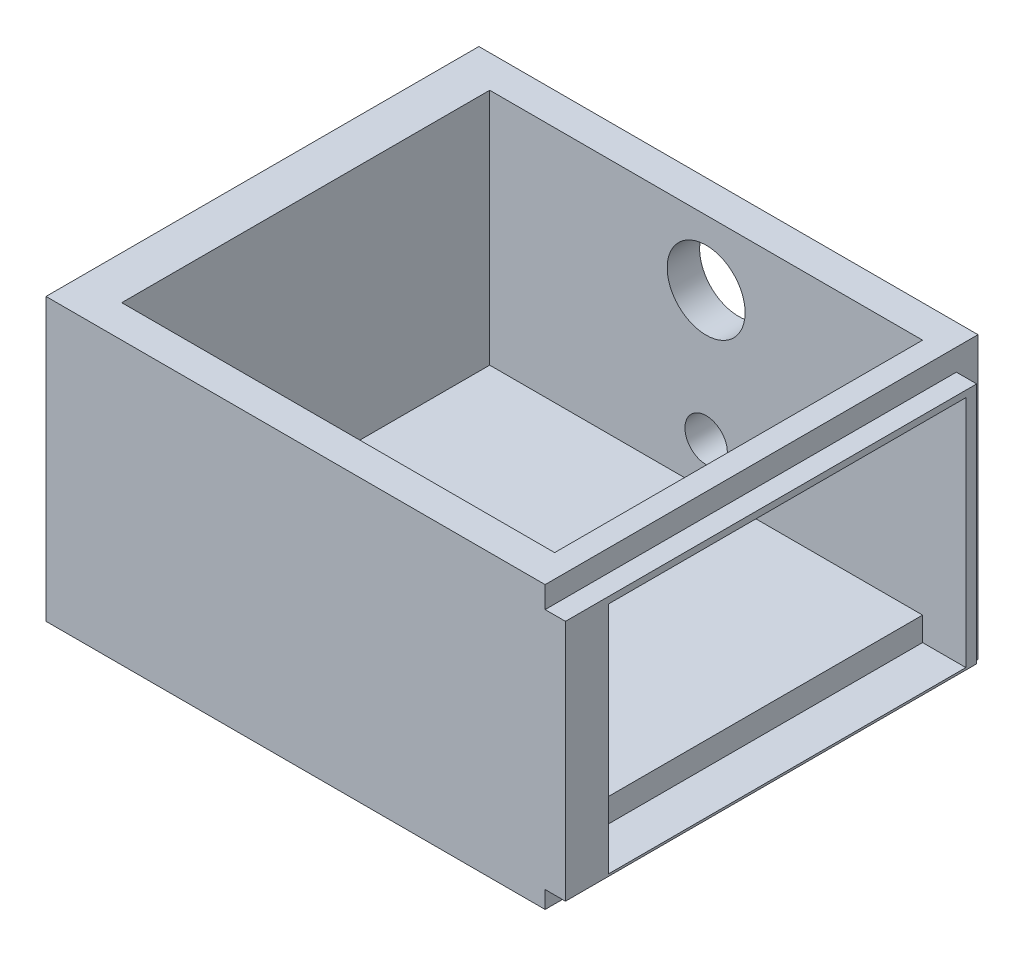
SolidWorks part; units mm, degrees
ref_plane "Front Plane" through (0, 0, 0) normal (0, 0, 1) x (1, 0, 0)
ref_plane "Top Plane" through (0, 0, 0) normal (0, 1, 0) x (1, 0, 0)
ref_plane "Right Plane" through (0, 0, 0) normal (1, 0, 0) x (0, 0, -1)
sketch "Sketch2" plane through (0, 0, 0) normal (0, 1, 0) x (1, 0, 0)
  line L1 (-60, -50) -> (60, -50)
  line L2 (-60, -50) -> (-60, 50)
  line L3 (-60, 50) -> (60, 50)
  line L4 (60, -50) -> (60, 50)
  line L5 (0, 50) -> (0, -50) construction
  line L6 (-60, 0) -> (60, 0) construction
  point P0 (0, 0)
  dimension "D1" = 100
  dimension "D2" = 120
extrude "Boss-Extrude2" add sketch "Sketch2" along normal blind 65
sketch "Sketch3" plane through (0, 65, 0) normal (0, 1, 0) x (1, 0, 0)
  line L1 (-50, -42.5) -> (50, -42.5)
  line L2 (-50, -42.5) -> (-50, 42.5)
  line L3 (-50, 42.5) -> (50, 42.5)
  line L4 (50, -42.5) -> (50, 42.5)
  line L5 (0, 42.5) -> (0, -42.5) construction
  line L6 (-50, 0) -> (50, 0) construction
  point P0 (0, 0)
  dimension "D1" = 100
  dimension "D2" = 85
extrude "Cut-Extrude1" cut sketch "Sketch3" against normal blind 55
sketch "Sketch6" plane through (0, 0, -42.5) normal (0, 0, 1) x (1, 0, 0)
  line L0 (50, 65) -> (-50, 65) construction
  line L2 (-50, 10) -> (-50, 65) construction
  line L4 (50, 10) -> (50, 65) construction
  circle A0 centre (0, 50) radius 9
  circle A1 centre (0, 20) radius 4.9
  dimension "D1" = 18
  dimension "D4" = 9.8
  dimension "D2" = 15
  dimension "D3" = 50
  dimension "D5" = 30
  dimension "D6" = 50
extrude "Cut-Extrude3" cut sketch "Sketch6" against normal blind 30
sketch "Sketch8" plane through (0, 0, 50) normal (0, 0, 1) x (1, 0, 0)
  line L0 (60, 4) -> (55.3, 4)
  line L1 (60, 65) -> (55.3, 65)
  line L2 (60, 65) -> (60, 60)
  line L3 (60, 60) -> (55.3, 60)
  line L4 (55.3, 65) -> (55.3, 60)
  line L5 (60, 4) -> (60, 0)
  line L6 (60, 0) -> (55.3, 0)
  line L7 (55.3, 4) -> (55.3, 0)
  line L9 (60, 65) -> (60, 0) construction
  line L10 (-60, 0) -> (60, 0) construction
  dimension "D1" = 0
  dimension "D2" = 0
  dimension "D3" = 5
  dimension "D4" = 4
  dimension "D5" = 4.7
  dimension "D6" = 4.7
extrude "Cut-Extrude6" cut sketch "Sketch8" against normal blind 95
sketch "Sketch9" plane through (60, 0, 0) normal (1, 0, 0) x (0, 0, -1)
  line L1 (50, 65) -> (45, 65)
  line L2 (50, 65) -> (50, 0)
  line L3 (50, 0) -> (45, 0)
  line L4 (45, 65) -> (45, 0)
extrude "Cut-Extrude7" cut sketch "Sketch9" against normal blind 4.7
sketch "Sketch10" plane through (60, 0, 0) normal (1, 0, 0) x (0, 0, -1)
  line L0 (-50, 60) -> (-50, 4) construction
  line L1 (-40, 58.5) -> (42.5, 58.5)
  line L2 (-40, 58.5) -> (-40, 4.5)
  line L3 (-40, 4.5) -> (42.5, 4.5)
  line L4 (42.5, 58.5) -> (42.5, 4.5)
  line L5 (45, 4) -> (-50, 4) construction
  dimension "D1" = 54
  dimension "D2" = 0.5
  dimension "D3" = 82.5
  dimension "D4" = 10
extrude "Cut-Extrude9" cut sketch "Sketch10" against normal blind 10
